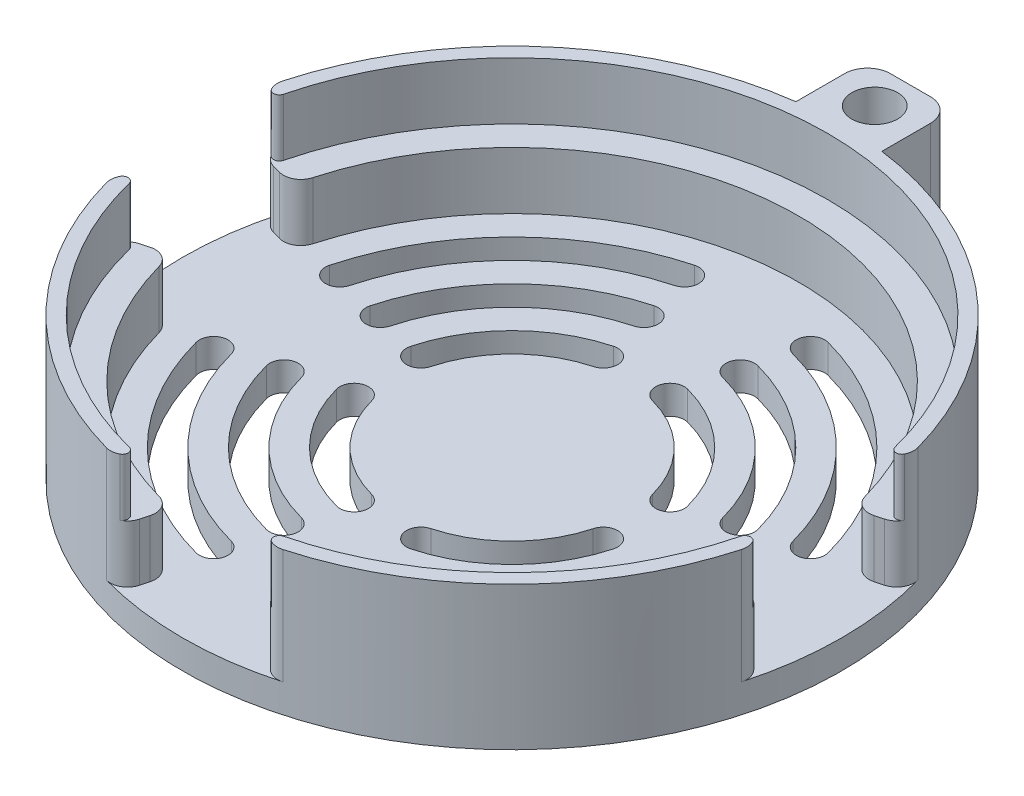
SolidWorks part; units mm, degrees
ref_plane "Alzado" through (0, 0, 0) normal (0, 0, 1) x (1, 0, 0)
ref_plane "Planta" through (0, 0, 0) normal (0, 1, 0) x (1, 0, 0)
ref_plane "Vista lateral" through (0, 0, 0) normal (1, 0, 0) x (0, 0, -1)
sketch "Croquis1" plane through (0, 0, 0) normal (0, 1, 0) x (1, 0, 0)
  circle A0 centre (0, 0) radius 57.5
  dimension "D1" = 115
extrude "Saliente-Extruir1" add sketch "Croquis1" along normal blind 25
sketch "Croquis2" plane through (0, 25, 0) normal (0, 1, 0) x (1, 0, 0)
  circle A0 centre (0, 0) radius 50
  dimension "D1" = 100
extrude "Cortar-Extruir1" cut sketch "Croquis2" against normal blind 20
sketch "Croquis3" plane through (0, 25, 0) normal (0, 1, 0) x (1, 0, 0)
  line L0 (0, 0) -> (0, 57.5) construction
  line L3 (-7.5, 57.0088) -> (-7.5, 69.5)
  line L4 (-7.5, 69.5) -> (7.5, 69.5)
  line L5 (7.5, 57.0088) -> (7.5, 69.5)
  circle A0 centre (0, 0) radius 57.5 construction
  arc A1 (7.5, 57.0088) -> (-7.5, 57.0088) centre (0, 0) ccw
  point P6 (0, 69.5)
  dimension "D1" = 12
  dimension "D2" = 15
extrude "Saliente-Extruir2" add sketch "Croquis3" against normal up to surface (25 mm away) up to face at (0, 0, 57.5)
fillet "Redondeo1" radius 4 2 edges at (7.5, 12.5, -69.5) (-7.5, 12.5, -69.5)
sketch "Croquis4" plane through (0, 25, 0) normal (0, 1, 0) x (1, 0, 0)
  circle A0 centre (0, 0) radius 55
  dimension "D1" = 110
extrude "Cortar-Extruir2" cut sketch "Croquis4" against normal blind 10
sketch "Croquis5" plane through (0, 5, 0) normal (0, 1, 0) x (1, 0, 0)
  line L0 (-1000, 0) -> (49000, 0) construction
  line L1 (0, -1000) -> (0, -30) construction
  line L2 (0, 0) -> (-24.6307, 91.923) construction
  line L3 (0, 0) -> (-48.2963, 12.941) construction
  line L4 (0, 0) -> (0, 49000) construction
  arc A2 (-5.1764, 19.3185) -> (-6.4705, 24.1481) centre (-5.8234, 21.7333) ccw
  arc A7 (-19.3185, 5.1764) -> (-24.1481, 6.4705) centre (-21.7333, 5.8234) cw
  arc A14 (-5.1764, 19.3185) -> (-19.3185, 5.1764) centre (0, 0) ccw
  arc A15 (-6.4705, 24.1481) -> (-24.1481, 6.4705) centre (0, 0) ccw
  circle A17 centre (0, 0) radius 50 construction
  arc A18 (-7.7646, 28.9778) -> (-28.9778, 7.7646) centre (0, 0) ccw
  arc A19 (-9.0587, 33.8074) -> (-33.8074, 9.0587) centre (0, 0) ccw
  arc A20 (-7.7646, 28.9778) -> (-9.0587, 33.8074) centre (-8.4116, 31.3926) ccw
  arc A21 (-33.8074, 9.0587) -> (-28.9778, 7.7646) centre (-31.3926, 8.4116) ccw
  arc A24 (-11.6469, 43.4667) -> (-43.4667, 11.6469) centre (0, 0) ccw
  arc A25 (-10.3528, 38.637) -> (-38.637, 10.3528) centre (0, 0) ccw
  arc A27 (-10.3528, 38.637) -> (-11.6469, 43.4667) centre (-10.9998, 41.0518) ccw
  arc A28 (-43.4667, 11.6469) -> (-38.637, 10.3528) centre (-41.0518, 10.9998) ccw
  dimension "D1" = 20
  dimension "D2" = 2.5
  dimension "D4" = 5
  dimension "D6" = 60
  dimension "D7" = 70
  dimension "D8" = 5
  dimension "D9" = 5
  dimension "D10" = 40
  dimension "D11" = 45
  dimension "D12" = 2.5
  dimension "D13" = 5
  dimension "D3" = 15
  dimension "D5" = 15
extrude "Cortar-Extruir3" cut sketch "Croquis5" against normal through all
pattern_circular "MatrizC1" count 4 over 360 about axis through (0, 0, 0) along (0, 1, 0) of "Cortar-Extruir3"
sketch "Croquis6" plane through (0, 25, 0) normal (0, 1, 0) x (1, 0, 0)
  line L0 (-71.1616, 16.4795) -> (-16.6363, 1.8695)
  line L1 (-15.7802, -1.6401) -> (-63.5779, -14.4475)
  line L2 (-15.7802, -1.6401) -> (-16.6363, 1.8695)
  line L3 (-63.5779, -14.4475) -> (-71.1616, 16.4795)
  arc A0 (-43.4667, 11.6469) -> (-38.637, 10.3528) centre (-41.0518, 10.9998) ccw construction
  arc A1 (-24.1481, 6.4705) -> (-19.3185, 5.1764) centre (-21.7333, 5.8234) ccw construction
  arc A2 (-19.3185, -5.1764) -> (-24.1481, -6.4705) centre (-21.7333, -5.8234) ccw construction
  arc A3 (-38.637, -10.3528) -> (-43.4667, -11.6469) centre (-41.0518, -10.9998) ccw construction
extrude "Cortar-Extruir4" cut sketch "Croquis6" against normal up to surface (20 mm away) up to face at (-27.597, 5, 27.597)
fillet "Redondeo2" radius 3 2 edges at (-48.8829, 10, -10.51) (-56.1353, 15, -12.4532)
fillet "Redondeo3" radius 3 2 edges at (-48.8829, 10, 10.51) (-56.1353, 15, 12.4532)
fillet "Redondeo4" radius 1 2 edges at (-53.7109, 20, 11.8383) (-53.7109, 20, -11.8383)
pattern_circular "MatrizC2" count 3 over 180 about axis through (0, 0, 0) along (0, 1, 0) of "Cortar-Extruir4", "Redondeo2", "Redondeo3", "Redondeo4"
sketch "Croquis7" plane through (0, 25, 0) normal (0, 1, 0) x (1, 0, 0)
  line L6 (-7.5, 69.5) -> (7.5, 69.5) construction
  line L8 (7.5, 57.0088) -> (7.5, 69.5) construction
  line L9 (-7.5, 57.0088) -> (-7.5, 69.5) construction
  line L10 (-7.5, 57.0088) -> (7.5, 69.5) construction
  line L11 (7.5, 57.0088) -> (-7.5, 69.5) construction
  circle A1 centre (0, 63.2544) radius 4
  dimension "D1" = 8
extrude "Cortar-Extruir5" cut sketch "Croquis7" against normal through all
